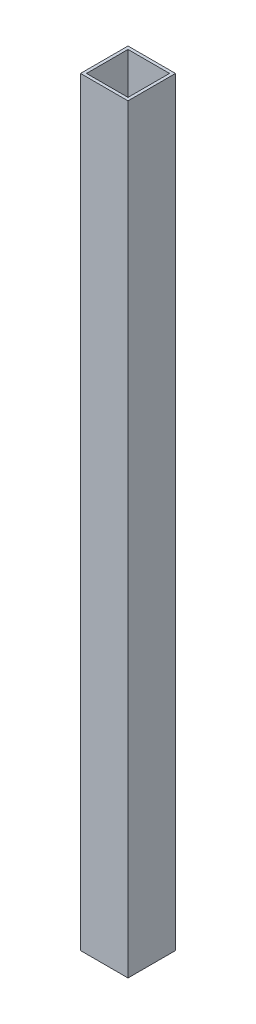
SolidWorks part; units mm, degrees
material "1060 Alloy"
ref_plane "Front Plane" through (0, 0, 0) normal (0, 0, 1) x (1, 0, 0)
ref_plane "Top Plane" through (0, 0, 0) normal (0, 1, 0) x (1, 0, 0)
ref_plane "Right Plane" through (0, 0, 0) normal (1, 0, 0) x (0, 0, -1)
sketch "Sketch1" plane through (0, 0, 0) normal (0, 1, 0) x (1, 0, 0)
  line L1 (12.7, 12.7) -> (-12.7, 12.7)
  line L2 (12.7, 12.7) -> (12.7, -12.7)
  line L3 (12.7, -12.7) -> (-12.7, -12.7)
  line L4 (-12.7, 12.7) -> (-12.7, -12.7)
  line L5 (12.7, 12.7) -> (-12.7, -12.7) construction
  line L6 (12.7, -12.7) -> (-12.7, 12.7) construction
  line L7 (11.1125, 11.1125) -> (-11.1125, 11.1125)
  line L8 (11.1125, 11.1125) -> (11.1125, -11.1125)
  line L9 (11.1125, -11.1125) -> (-11.1125, -11.1125)
  line L10 (-11.1125, 11.1125) -> (-11.1125, -11.1125)
  line L11 (11.1125, 11.1125) -> (-11.1125, -11.1125) construction
  line L12 (11.1125, -11.1125) -> (-11.1125, 11.1125) construction
  point P0 (0, 0)
  point P6 (0, 0)
  dimension "D1" = 25.4
  dimension "D2" = 25.4
  dimension "D3" = 1.5875
  dimension "D4" = 1.5875
extrude "Boss-Extrude1" add sketch "Sketch1" along normal blind 406.4
